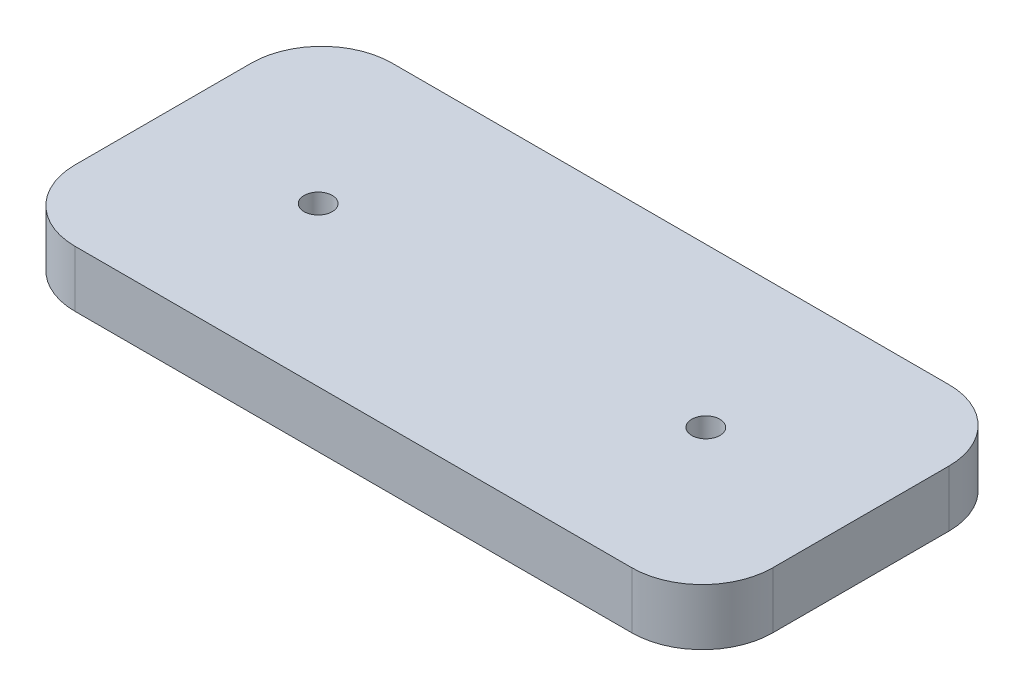
SolidWorks part; units mm, degrees
ref_plane "Front Plane" through (0, 0, 0) normal (0, 0, 1) x (1, 0, 0)
ref_plane "Top Plane" through (0, 0, 0) normal (0, 1, 0) x (1, 0, 0)
ref_plane "Right Plane" through (0, 0, 0) normal (1, 0, 0) x (0, 0, -1)
sketch "Sketch1" plane through (0, 0, 0) normal (0, 1, 0) x (1, 0, 0)
  line L0 (49.5, 45) -> (49.5, 0) construction
  line L1 (0, 0) -> (99, 0)
  line L2 (0, 0) -> (0, 45)
  line L3 (0, 45) -> (99, 45)
  line L4 (99, 0) -> (99, 45)
  line L5 (0, 0) -> (99, 45) construction
  line L6 (0, 45) -> (99, 0) construction
  circle A0 centre (22, 22.5) radius 2
  circle A2 centre (77, 22.5) radius 2
  point P4 (49.5, 22.5)
  dimension "D4" = 4
  dimension "D1" = 99
  dimension "D2" = 45
  dimension "D3" = 55
  dimension "D5" = 22.5
extrude "Boss-Extrude1" add sketch "Sketch1" along normal blind 8
fillet "Fillet1" radius 10 4 edges at (0, 4, -45) (99, 4, -45) (99, 4, 0) (0, 4, 0)
